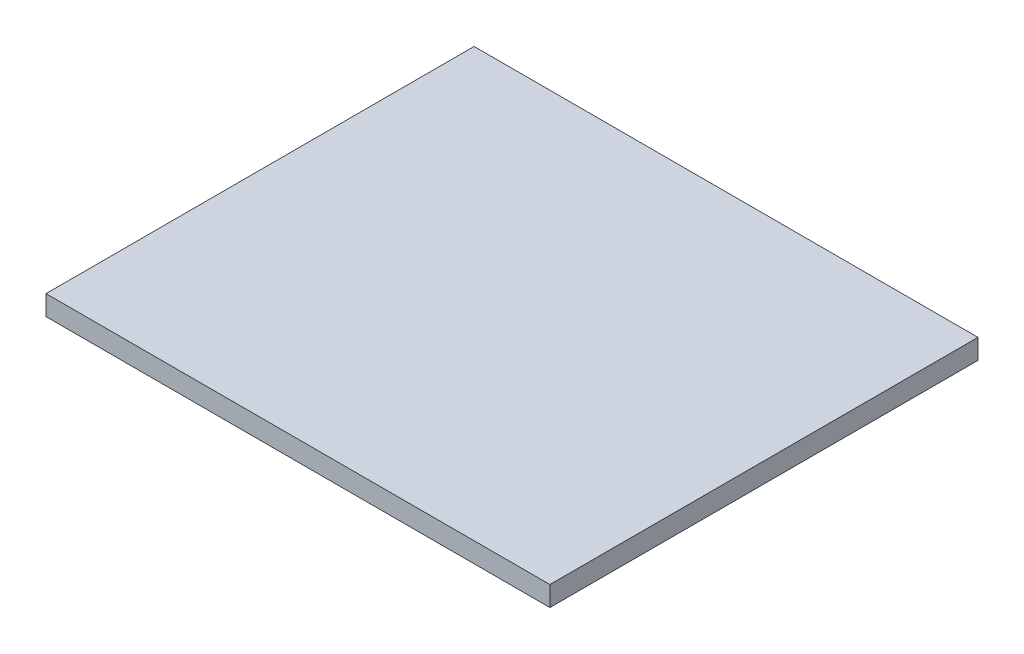
SolidWorks part; units mm, degrees
ref_plane "Front" through (0, 0, 0) normal (0, 0, 1) x (1, 0, 0)
ref_plane "Top" through (0, 0, 0) normal (0, 1, 0) x (1, 0, 0)
ref_plane "Right" through (0, 0, 0) normal (1, 0, 0) x (0, 0, -1)
sketch "Sketch1" plane through (0, 0, 0) normal (0, 1, 0) x (1, 0, 0)
  line L1 (0, 0) -> (75.8, 0)
  line L2 (0, 0) -> (0, -64.4)
  line L3 (0, -64.4) -> (75.8, -64.4)
  line L4 (75.8, 0) -> (75.8, -64.4)
  dimension "D1" = 64.4
  dimension "D2" = 75.8
extrude "Boss-Extrude1" add sketch "Sketch1" along normal blind 3 contours L1 L4 L3 L2
